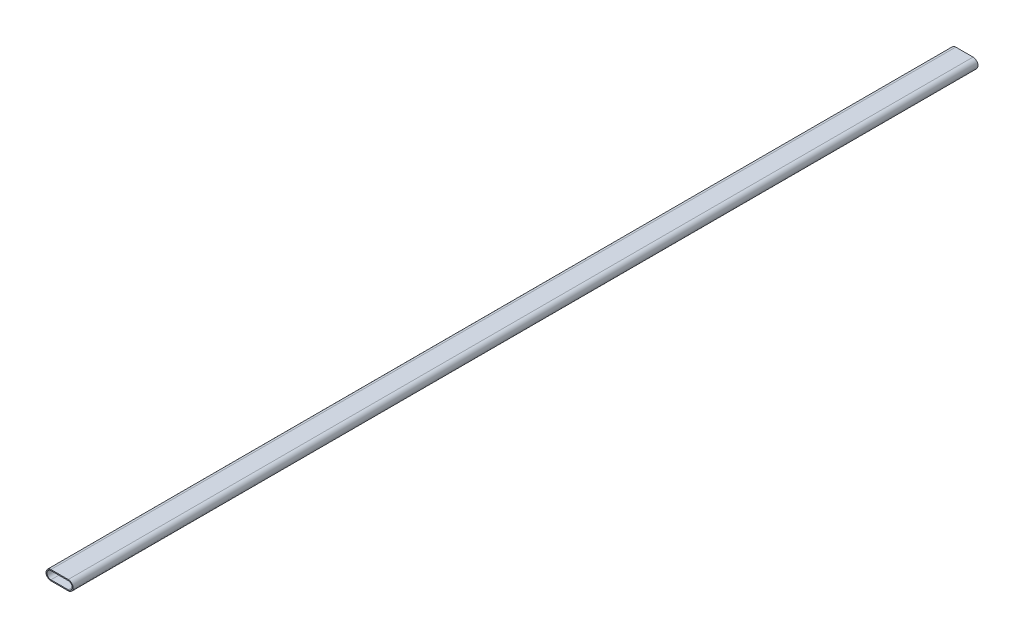
SolidWorks part; units mm, degrees
ref_plane "Front Plane" through (0, 0, 0) normal (0, 0, 1) x (1, 0, 0)
ref_plane "Top Plane" through (0, 0, 0) normal (0, 1, 0) x (1, 0, 0)
ref_plane "Right Plane" through (0, 0, 0) normal (1, 0, 0) x (0, 0, -1)
sketch "Sketch1" plane through (0, 0, 0) normal (0, 0, 1) x (1, 0, 0)
  line L0 (0, 0) -> (21, 0) construction
  line L1 (0, 6) -> (21, 6)
  line L2 (0, -6) -> (21, -6)
  line L3 (0, 4.8) -> (21, 4.8)
  line L4 (0, -4.8) -> (21, -4.8)
  arc A0 (0, 6) -> (0, -6) centre (0, 0) ccw
  arc A1 (21, -6) -> (21, 6) centre (21, 0) ccw
  arc A2 (21, -4.8) -> (21, 4.8) centre (21, 0) ccw
  arc A3 (0, 4.8) -> (0, -4.8) centre (0, 0) ccw
  point P3 (10.5, 0)
  dimension "D1" = 12
  dimension "D2" = 21
  dimension "D3" = 1.2
extrude "Boss-Extrude1" add sketch "Sketch1" along normal blind 1100
